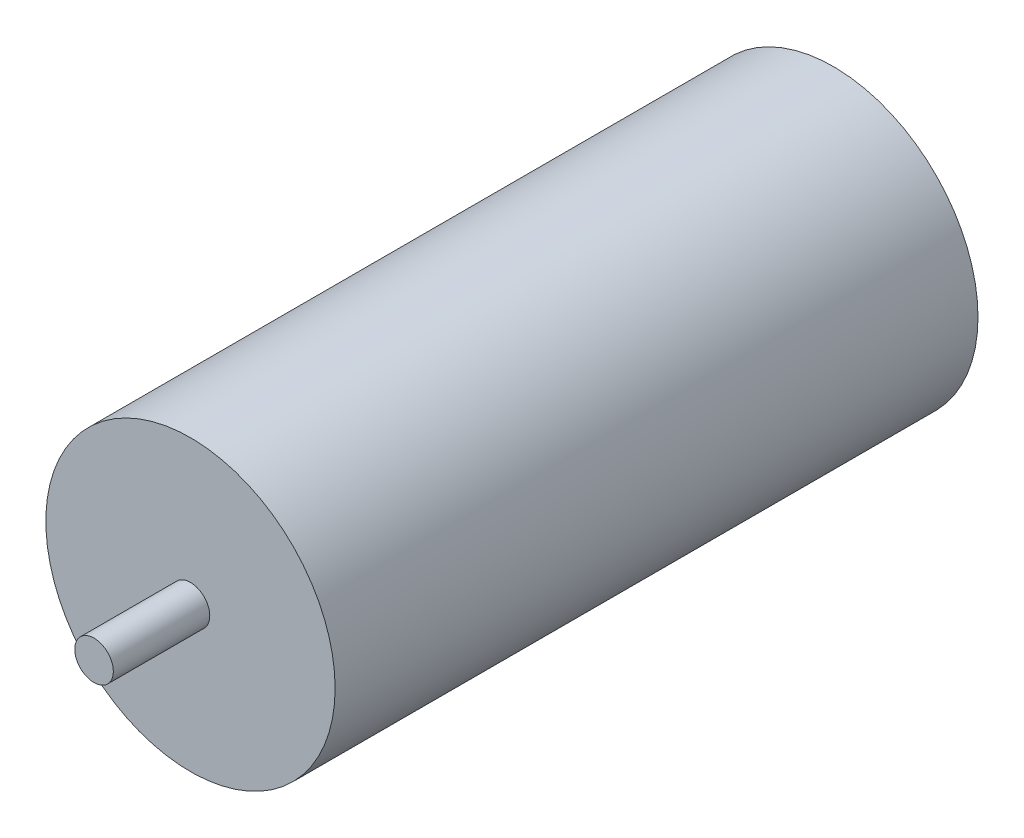
SolidWorks part; units mm, degrees
ref_plane "Front Plane" through (0, 0, 0) normal (0, 0, 1) x (1, 0, 0)
ref_plane "Top Plane" through (0, 0, 0) normal (0, 1, 0) x (1, 0, 0)
ref_plane "Right Plane" through (0, 0, 0) normal (1, 0, 0) x (0, 0, -1)
sketch "Sketch1" plane through (0, 0, 0) normal (0, 0, 1) x (1, 0, 0)
  circle A0 centre (0, 0) radius 22.5
  dimension "D1" = 45
extrude "Boss-Extrude1" add sketch "Sketch1" along normal blind 100
sketch "Sketch2" plane through (0, 0, 100) normal (0, 0, 1) x (1, 0, 0)
  circle A0 centre (0, 0) radius 3
  dimension "D1" = 6
extrude "Boss-Extrude2" add sketch "Sketch2" along normal blind 15
